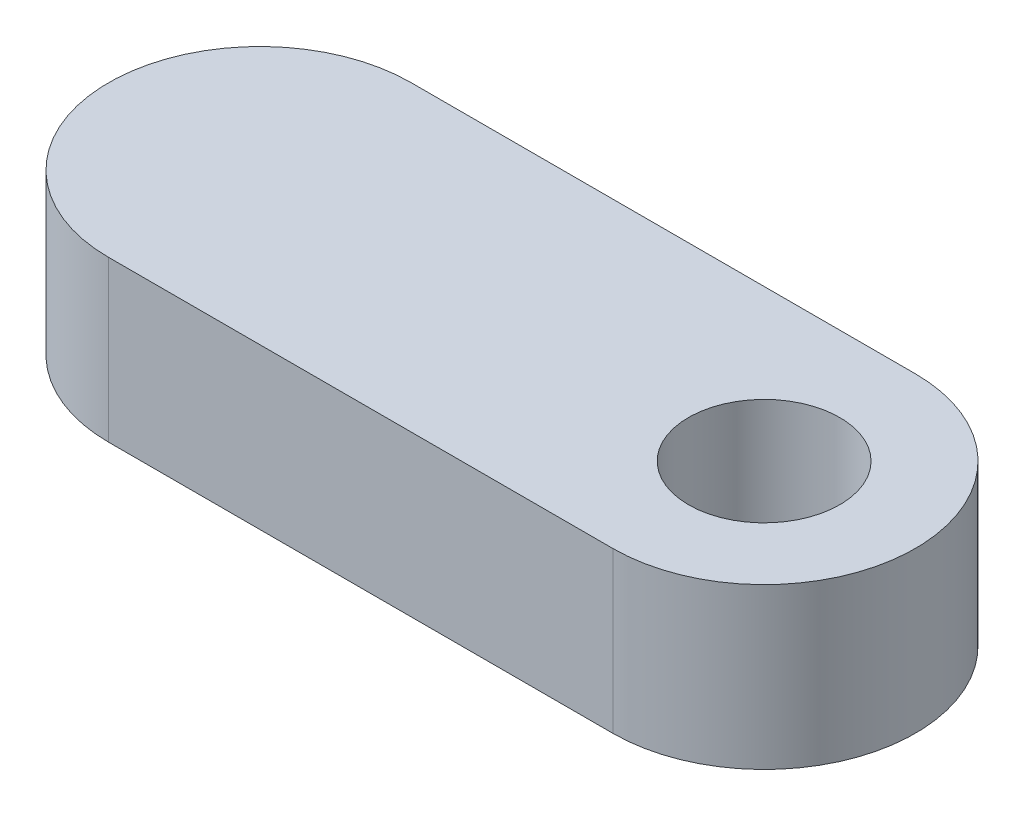
SolidWorks part; units mm, degrees
ref_plane "Front Plane" through (0, 0, 0) normal (0, 0, 1) x (1, 0, 0)
ref_plane "Top Plane" through (0, 0, 0) normal (0, 1, 0) x (1, 0, 0)
ref_plane "Right Plane" through (0, 0, 0) normal (1, 0, 0) x (0, 0, -1)
sketch "Sketch1" plane through (0, 0, 0) normal (0, 1, 0) x (1, 0, 0)
  line L0 (-5, 3) -> (5, 3)
  line L2 (5, -3) -> (-5, -3)
  line L3 (-8.8, 0) -> (8.8, 0) construction
  line L4 (0, -3.3) -> (0, 3.3) construction
  arc A0 (-5, 3) -> (-5, -3) centre (-5, 0) ccw
  arc A1 (5, 3) -> (5, -3) centre (5, 0) cw
  circle A2 centre (5, 0) radius 1.5
  point P6 (0, 0)
  dimension "D4" = 3
  dimension "D1" = 6
  dimension "D2" = 10
  dimension "D3" = 5
extrude "Boss-Extrude1" add sketch "Sketch1" along normal blind 3.175
equation "\"D3@Sketch1\"=\"D2@Sketch1\"/2"
